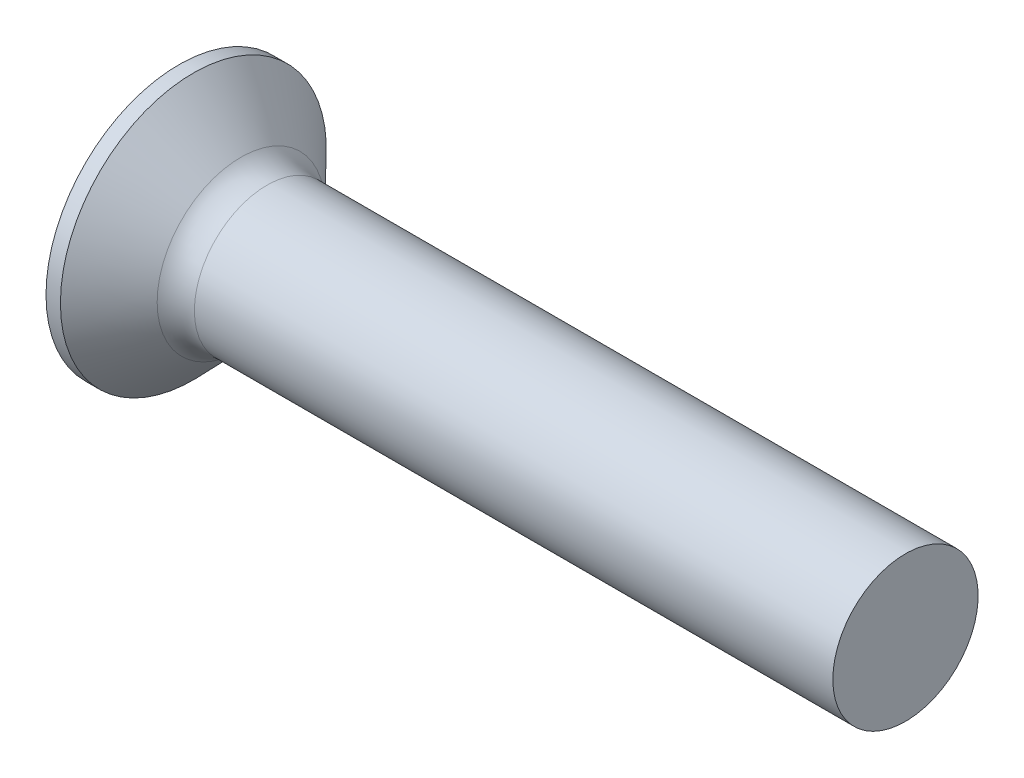
SolidWorks part; units mm, degrees
revolve "Base-Revolve" add sketch "BodySke"
sketch "BodySke" plane through (0, 0, 0) normal (0, 0, 1) x (1, 0, 0)
  line L0 (0, 0) -> (0, 9.15)
  line L1 (0, 9.15) -> (0.9924, 9.15)
  line L2 (5, 5) -> (50, 5)
  line L3 (50, 5) -> (50, 0)
  line L4 (50, 0) -> (0, 0)
  line L5 (-6.35, 0) -> (82.55, 0) construction
  line L6 (5, -5) -> (50, -5) construction
  line L7 (0.9924, -9.15) -> (5, -5) construction
  line L8 (0.9924, 9.15) -> (5, 5)
  line L9 (0, -9.15) -> (0.9924, -9.15) construction
  line L10 (6.5, 6.5875) -> (6.5, -2.9375) construction
  line L11 (0, 6.35) -> (0, -3.175) construction
cosmetic thread "ThreadCosmetic" [suppressed]
fillet "Fillet1" radius 2.5 1 edges at (5, 0, 5)
ref_plane "Plane1" through (0, 0, 0) normal (0, 0, 1) x (1, 0, 0)
ref_plane "Plane2" through (0, 0, 0) normal (0, 1, 0) x (1, 0, 0)
ref_plane "Plane3" through (0, 0, 0) normal (1, 0, 0) x (0, 0, -1)
other "Configuration Table"
sketch "Sketch3" plane through (0, 0, 0) normal (-1, 0, 0) x (0, 0, 1)
  line L0 (-1.08, 4.9) -> (1.08, 4.9)
  line L1 (1.08, 4.9) -> (1.08, -4.9)
  line L2 (1.08, -4.9) -> (-1.08, -4.9)
  line L3 (-1.08, -4.9) -> (-1.08, 4.9)
  dimension "D1" = 2.2
  dimension "D2" = 0.515
ref_plane "Plane4" through (5.64, 0, 0) normal (-1, 0, 0) x (0, 0, 1)
sketch "Sketch4" plane through (5.64, 0, 0) normal (-1, 0, 0) x (0, 0, 1)
  line L0 (-1.08, 2.088) -> (1.08, 2.088)
  line L3 (1.08, 2.088) -> (1.08, -2.088)
  line L4 (1.08, -2.088) -> (-1.08, -2.088)
  line L5 (-1.08, -2.088) -> (-1.08, 2.088)
  dimension "D2" = 1.8971
  dimension "D1" = 1.03
  dimension "D4" = 0.9486
  dimension "D3" = 0.515
loft "Recess" cut profiles "Sketch3", "Sketch4"
pattern_circular "RecPat" count 2 every 90 about axis through (0, 0, 0) along (1, 0, 0) of "Recess"
sketch "RecCorSke" plane through (0, 0, 0) normal (0, 0, 1) x (1, 0, 0)
  line L0 (-3.175, 0) -> (15.875, 0) construction
  line L2 (0, 0) -> (0, 2.3249)
  line L3 (0, 2.3249) -> (5.64, 1.9305)
  line L4 (5.64, 1.9305) -> (6.2673, 0)
  line L5 (6.2673, 0) -> (0, 0)
  dimension "Depth" = 2.51
  dimension "Draft_angle" = 4
  dimension "Bottom_angle" = 18
revolve "RecessCore" cut sketch "RecCorSke" angle 360 about L0
sketch "ThdSchSke" plane through (0, 0, 0) normal (0, 0, 1) x (1, 0, 0)
  line L0 (6.5, -3.9624) -> (5.7735, -5)
  line L1 (6.5, -3.9624) -> (7.2265, -5)
  line L2 (7.2265, -5) -> (7.2265, -6.25)
  line L3 (-3.175, 0) -> (5.1513, 0) construction
  line L5 (7.2265, -6.25) -> (5.7735, -6.25)
  line L6 (5.7735, -6.25) -> (5.7735, -5)
  line L7 (0, 9.15) -> (0, -9.15) construction
  dimension "Thread_minor" = 3.22
  dimension "Diameter" = 4
  dimension "Start" = 3.4
revolve "ThreadSchematic" [suppressed] cut sketch "ThdSchSke" angle 360 about L3
pattern_linear "ThdSchPat" [suppressed]
equation "\"D1@Sketch3\" = \"Cross_dia@Sketch3\" / 2"
equation "\"D2@Sketch3\" = \"Cross_width@Sketch3\" / 2"
equation "\"Depth@RecCorSke\" = \"Cross_depth@Plane4\""
equation "\"D1@Sketch4\" = \"Cross_width@Sketch3\""
equation "\"D2@Sketch4\" = \"Cross_dia@Sketch3\" - 2.0 * \"Cross_depth@Plane4\" * tan(26.5  * 0.017453292)"
equation "\"D3@Sketch4\" = \"D1@Sketch4\" / 2"
equation "\"D4@Sketch4\" = \"D2@Sketch4\" / 2"
equation "\"Thread_length@ThreadCosmetic\" = ((sgn( (\"Length@BodySke\" - \"Advance@BodySke\" * 1.0 - \"Head_ht@BodySke\" ) - \"Thread_nom@BodySke\" )-1)*( (\"Length@BodySke\" - \"Advance@BodySke\" * 1.0 - \"Head_ht@BodySke\" ) - \"Thread_nom@BodySke\" ))/-2+ \"Thread_nom@BodySke\""
equation "\"Thread_minor@ThdSchSke\" = \"Thread_minor@ThreadCosmetic\""
equation "\"Diameter@ThdSchSke\" = \"Diameter@BodySke\""
equation "\"Overcut@ThdSchSke\" = \"Diameter@BodySke\" * 1.25"
equation "\"Start@ThdSchSke\" = 0.000001 + \"Length@BodySke\" - \"Thread_length@ThreadCosmetic\"  '---Countersunk---"
equation "\"Num_threads@ThdSchPat\" = int( \"Thread_length@ThreadCosmetic\" / \"Advance@BodySke\" + 0.999 )  + 1"
equation "\"Advance@ThdSchPat\" = \"Thread_length@ThreadCosmetic\" /  (\"Num_threads@ThdSchPat\" - 1) 'relax it"
